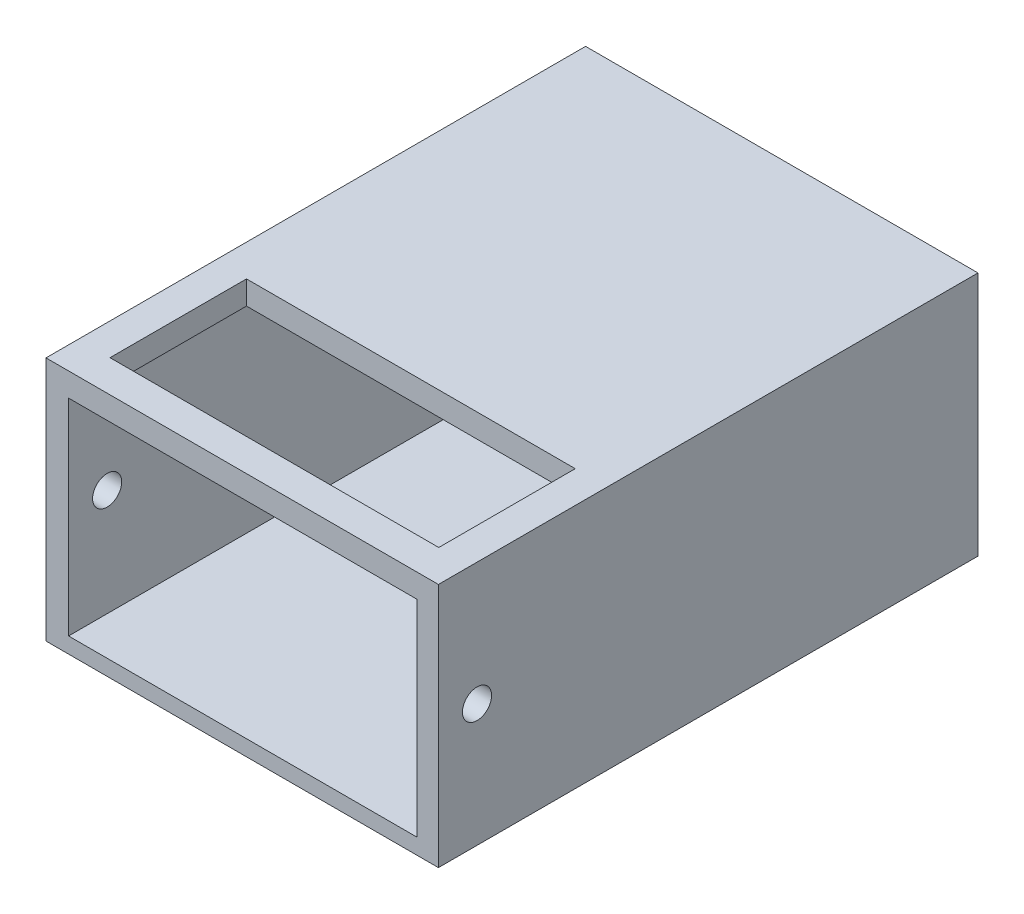
SolidWorks part; units mm, degrees
ref_plane "Front Plane" through (0, 0, 0) normal (0, 0, 1) x (1, 0, 0)
ref_plane "Top Plane" through (0, 0, 0) normal (0, 1, 0) x (1, 0, 0)
ref_plane "Right Plane" through (0, 0, 0) normal (1, 0, 0) x (0, 0, -1)
sketch "Sketch1" plane through (0, 0, 0) normal (0, 1, 0) x (1, 0, 0)
  line L1 (-20, 27.5) -> (20, 27.5)
  line L2 (-20, 27.5) -> (-20, -27.5)
  line L3 (-20, -27.5) -> (20, -27.5)
  line L4 (20, 27.5) -> (20, -27.5)
  line L5 (-20, 27.5) -> (20, -27.5) construction
  line L6 (-20, -27.5) -> (20, 27.5) construction
  point P0 (0, 0)
  dimension "D1" = 40
  dimension "D2" = 55
extrude "Boss-Extrude1" add sketch "Sketch1" along normal blind 25
sketch "Sketch2" plane through (0, 0, 27.5) normal (0, 0, 1) x (1, 0, 0)
  line L0 (-20, 25) -> (20, 25) construction
  line L1 (-17.7, 22.6) -> (17.8, 22.6)
  line L2 (-17.7, 22.6) -> (-17.7, 1.6)
  line L3 (-17.7, 1.6) -> (17.8, 1.6)
  line L4 (17.8, 22.6) -> (17.8, 1.6)
  line L5 (-17.7, 22.6) -> (17.8, 1.6) construction
  line L6 (-17.7, 1.6) -> (17.8, 22.6) construction
  line L7 (-20, 25) -> (-20, 0) construction
  point P0 (0.05, 12.1)
  dimension "D1" = 35.5
  dimension "D2" = 21
  dimension "D3" = 2.4
  dimension "D4" = 2.3
extrude "Cut-Extrude1" cut sketch "Sketch2" against normal blind 52.5
sketch "Sketch3" plane through (-20, 0, 0) normal (-1, 0, 0) x (0, 0, 1)
  circle A0 centre (23.567, 12.5) radius 1.4851
extrude "Cut-Extrude2" cut sketch "Sketch3" against normal blind 52.5
sketch "Sketch5" plane through (0, 25, 0) normal (0, 1, 0) x (1, 0, 0)
  line L1 (-16.755, -10.3075) -> (16.755, -10.3075)
  line L2 (-16.755, -10.3075) -> (-16.755, -24.2206)
  line L3 (-16.755, -24.2206) -> (16.755, -24.2206)
  line L4 (16.755, -10.3075) -> (16.755, -24.2206)
  line L5 (-16.755, -10.3075) -> (16.755, -24.2206) construction
  line L6 (-16.755, -24.2206) -> (16.755, -10.3075) construction
  point P0 (0, -17.264)
extrude "Cut-Extrude3" cut sketch "Sketch5" against normal blind 20
